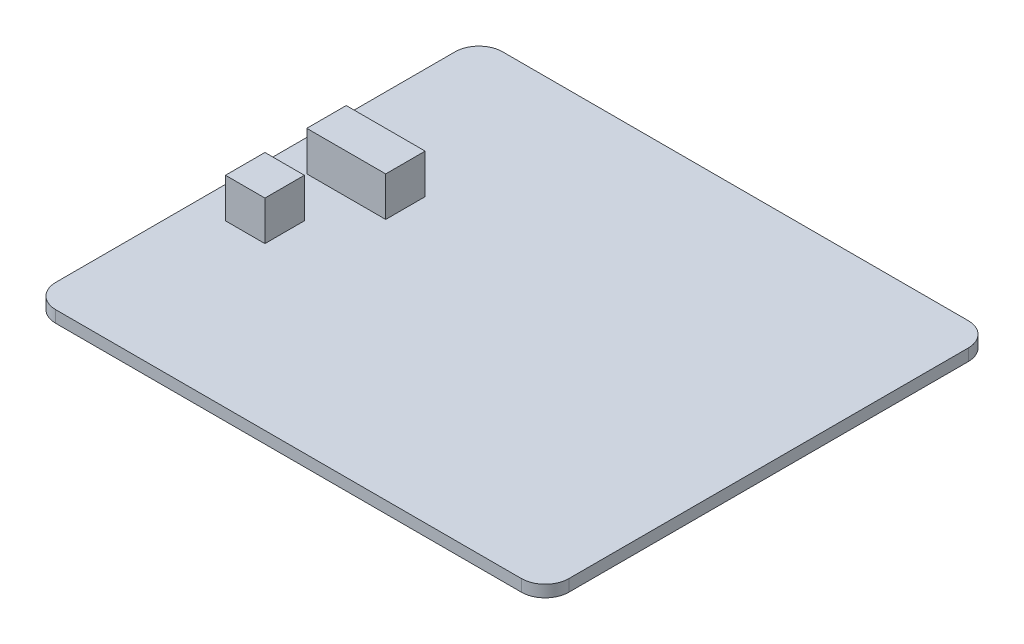
SolidWorks part; units mm, degrees
ref_plane "Front Plane" through (0, 0, 0) normal (0, 0, 1) x (1, 0, 0)
ref_plane "Top Plane" through (0, 0, 0) normal (0, 1, 0) x (1, 0, 0)
ref_plane "Right Plane" through (0, 0, 0) normal (1, 0, 0) x (0, 0, -1)
sketch "Sketch1" plane through (0, 0, 0) normal (0, 1, 0) x (1, 0, 0)
  line L1 (0, 0) -> (65, 0)
  line L2 (0, 0) -> (0, 56.6)
  line L3 (0, 56.6) -> (65, 56.6)
  line L4 (65, 0) -> (65, 56.6)
  dimension "D1" = 65
  dimension "D2" = 56.6
extrude "Boss-Extrude1" add sketch "Sketch1" along normal blind 1.5
fillet "Fillet1" radius 3 4 edges at (0, 0.75, -56.6) (65, 0.75, -56.6) (65, 0.75, 0) (0, 0.75, 0)
sketch "Sketch2" plane through (0, 1.5, 0) normal (0, 1, 0) x (1, 0, 0)
  line L0 (3, 0) -> (62, 0) construction
  line L1 (4, 25.5) -> (9, 25.5)
  line L2 (4, 25.5) -> (4, 20.5)
  line L3 (4, 20.5) -> (9, 20.5)
  line L4 (9, 25.5) -> (9, 20.5)
  line L5 (0, 53.6) -> (0, 3) construction
  line L7 (14, 35.8) -> (4, 35.8)
  line L8 (14, 35.8) -> (14, 30.8)
  line L9 (14, 30.8) -> (4, 30.8)
  line L10 (4, 35.8) -> (4, 30.8)
  point P4 (4, 23)
  point P13 (4, 33.3)
  dimension "D1" = 23
  dimension "D2" = 5
  dimension "D3" = 4
  dimension "D4" = 33.3
  dimension "D5" = 10
extrude "Boss-Extrude2" add sketch "Sketch2" along normal blind 5
other "Freeze***"
